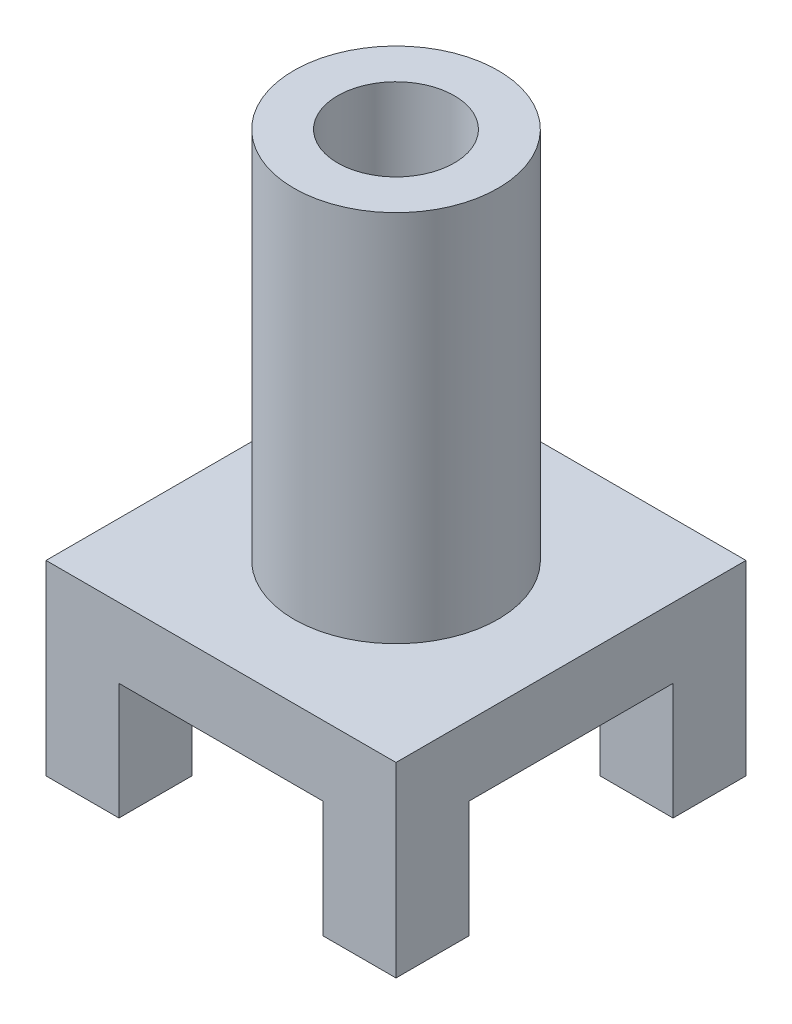
SolidWorks part; units mm, degrees
ref_plane "Alzado" through (0, 0, 0) normal (0, 0, 1) x (1, 0, 0)
ref_plane "Planta" through (0, 0, 0) normal (0, 1, 0) x (1, 0, 0)
ref_plane "Vista lateral" through (0, 0, 0) normal (1, 0, 0) x (0, 0, -1)
sketch "Croquis1" plane through (0, 0, 0) normal (0, 1, 0) x (1, 0, 0)
  line L1 (-30, 30) -> (30, 30)
  line L2 (-30, 30) -> (-30, -30)
  line L3 (-30, -30) -> (30, -30)
  line L4 (30, 30) -> (30, -30)
  line L5 (-30, 30) -> (30, -30) construction
  line L6 (-30, -30) -> (30, 30) construction
  point P0 (0, 0)
  dimension "D1" = 60
  dimension "D2" = 60
extrude "Saliente-Extruir1" add sketch "Croquis1" along normal blind 32
sketch "Croquis2" plane through (0, 0, 30) normal (0, 0, 1) x (1, 0, 0)
  line L0 (-30, 0) -> (30, 0) construction
  line L1 (-17.5, 0) -> (17.5, 0)
  line L2 (-17.5, 0) -> (-17.5, 20)
  line L3 (-17.5, 20) -> (17.5, 20)
  line L4 (17.5, 0) -> (17.5, 20)
  dimension "D1" = 35
  dimension "D2" = 20
  dimension "D3" = 17.5
extrude "Cortar-Extruir1" cut sketch "Croquis2" against normal through all
sketch "Croquis3" plane through (30, 0, 0) normal (1, 0, 0) x (0, 0, -1)
  line L0 (-30, 0) -> (30, 0) construction
  line L1 (-17.5, 0) -> (17.5, 0)
  line L2 (-17.5, 0) -> (-17.5, 20)
  line L3 (-17.5, 20) -> (17.5, 20)
  line L4 (17.5, 0) -> (17.5, 20)
  dimension "D1" = 20
  dimension "D2" = 35
  dimension "D3" = 17.5
extrude "Cortar-Extruir2" cut sketch "Croquis3" against normal through all
sketch "Croquis4" plane through (0, 32, 0) normal (0, 1, 0) x (1, 0, 0)
  circle A0 centre (0, 0) radius 17.5
extrude "Saliente-Extruir2" add sketch "Croquis4" along normal blind 64 contours A0
sketch "Croquis5" plane through (0, 96, 0) normal (0, 1, 0) x (1, 0, 0)
  circle A0 centre (0, 0) radius 10
extrude "Cortar-Extruir3" cut sketch "Croquis5" against normal through all
